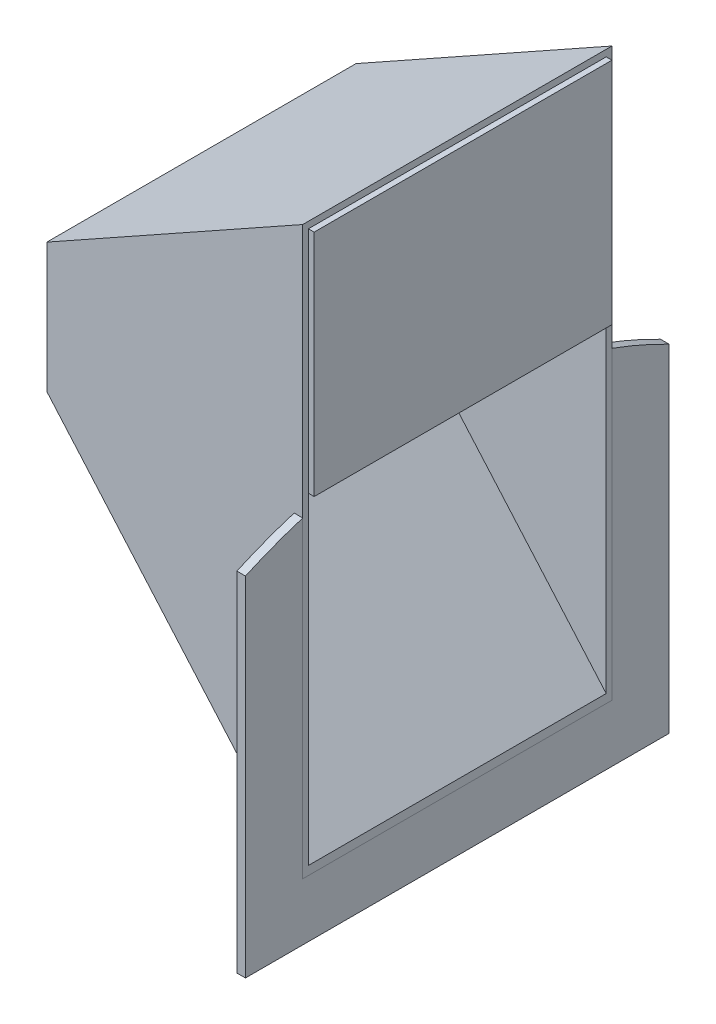
SolidWorks part; units mm, degrees
ref_plane "Front Plane" through (0, 0, 0) normal (0, 0, 1) x (1, 0, 0)
ref_plane "Top Plane" through (0, 0, 0) normal (0, 1, 0) x (1, 0, 0)
ref_plane "Right Plane" through (0, 0, 0) normal (1, 0, 0) x (0, 0, -1)
sketch "Sketch1" plane through (0, 0, 0) normal (0, 0, 1) x (1, 0, 0)
  line L0 (0, 111.4633) -> (0, 214.4714) construction
  line L3 (-9.7568, 226.7317) -> (-85.1358, 226.7317) construction
  line L10 (0, 214.4714) -> (-89.3791, 164.4633)
  line L11 (-89.3791, 164.4633) -> (-89.3791, 119.2634)
  line L12 (0, 16.5557) -> (-89.3791, 119.2634)
  line L14 (0, 214.4714) -> (0, 16.5557)
  line L15 (-44.6896, 189.4673) -> (-44.6896, 226.7317) construction
  line L21 (-9.7568, 226.7317) -> (-9.7568, 209.0124) construction
  line L22 (-85.1358, 226.7317) -> (-85.1358, 166.8375) construction
extrude "Boss-Extrude1" add sketch "Sketch1" along normal blind 108
shell "Shell1" thickness 2
ref_plane "Plane1" through (0, 230, 0) normal (0, 1, 0) x (1, 0, 0)
sketch "Sketch3" plane through (0, 230, 0) normal (0, 1, 0) x (1, 0, 0)
  line L0 (-89.3791, -54) -> (0, -54) construction
  line L1 (-89.3791, -108) -> (-89.3791, 0) construction
  line L2 (0, -108) -> (0, 0) construction
  circle A0 centre (-44.6896, -54) radius 38
  circle A1 centre (-44.6896, -54) radius 36
  dimension "D1" = 76
  dimension "D2" = 2
sketch "Sketch5" plane through (0, 0, 0) normal (1, 0, 0) x (0, 0, -1)
  line L0 (-106, 19.6024) -> (-106, 212.1796) construction
  line L1 (-2, 212.1796) -> (-106, 212.1796)
  line L2 (-2, 212.1796) -> (-2, 132.1796)
  line L3 (-2, 132.1796) -> (-106, 132.1796)
  line L4 (-106, 212.1796) -> (-106, 132.1796)
  line L5 (-54, 212.1796) -> (-54, 132.1796) construction
  circle A0 centre (-54, 172.1796) radius 30
  line M10 (-2, 212.1796) -> (-2, 19.6024)
  line M12 (-106, 19.6024) -> (-106, 212.1796)
  line M13 (-106, 212.1796) -> (-2, 212.1796)
  dimension "D1" = 60
  dimension "D2" = 80
extrude "Boss-Extrude3" add sketch "Sketch5" along normal blind 2 separate body contours A0 L5 L3 L2 | L1 L5 A0 M10 | L5 L4 A0 M13 | L5 A0 L3 M12
sketch "Sketch6" plane through (0, 0, 0) normal (1, 0, 0) x (0, 0, -1)
  line L0 (-108, 164.4633) -> (-108, 119.2634) construction
  line L1 (0, 16.5557) -> (-108, 16.5557)
  line L2 (0, 16.5557) -> (0, 123.0252)
  line L4 (-108, 16.5557) -> (-108, 125.7061)
  line L5 (-128, -3.4443) -> (-128, 118.1447)
  line L7 (20, -3.4443) -> (20, 114.275)
  line L8 (20, -3.4443) -> (-128, -3.4443)
  line L10 (-128, -3.4443) -> (-128, 146.2087) construction
  line L11 (20, 142.5349) -> (-128, 146.2087) construction
  line L12 (20, -3.4443) -> (20, 142.5349) construction
  line L13 (0, 123.0252) -> (-108, 125.7061) construction
  arc A0 (112, -36.7747) -> (-228, -36.7747) centre (-58, -36.7747) ccw construction
  arc A1 (20, 114.275) -> (0, 123.0252) centre (-58, -36.7747) ccw
  arc A2 (-108, 125.7061) -> (-128, 118.1447) centre (-58, -36.7747) ccw
  dimension "D1" = 20
extrude "Boss-Extrude9" add sketch "Sketch6" against normal blind 3 separate body
